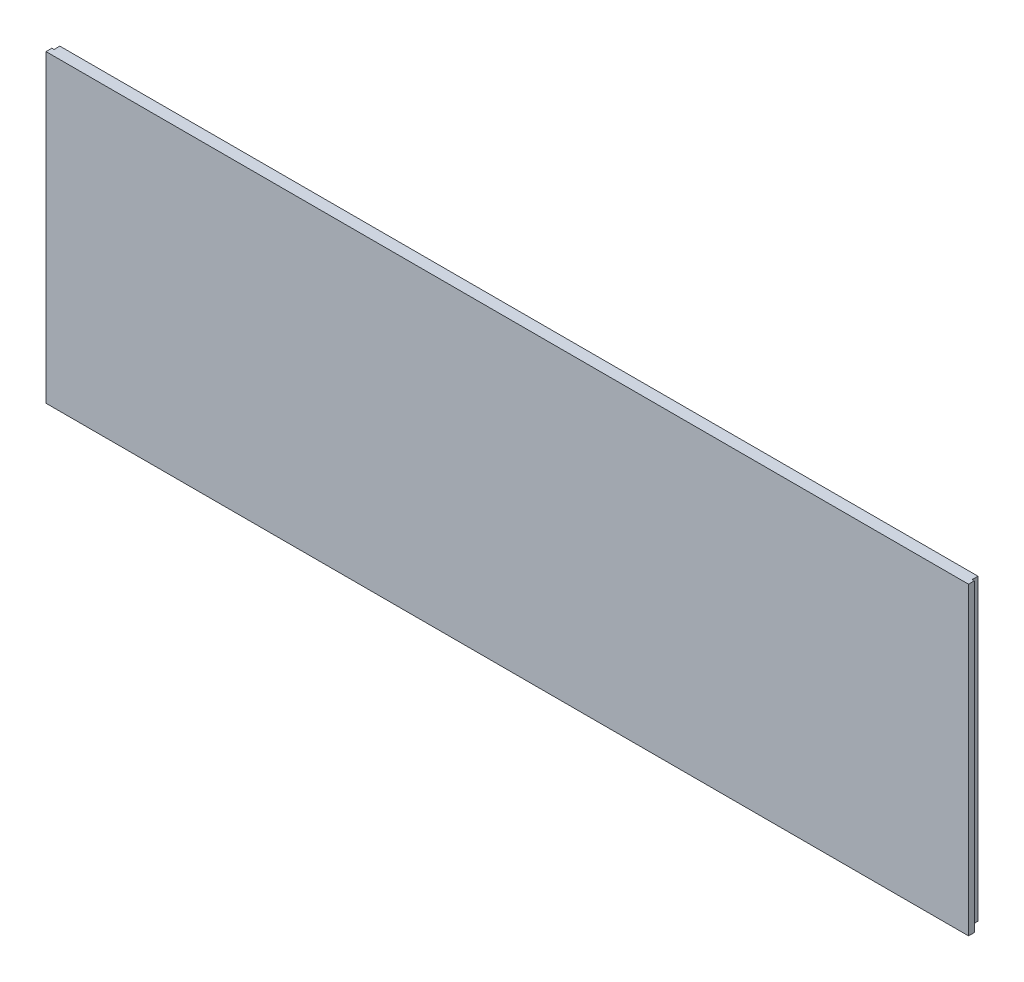
SolidWorks part; units mm, degrees
ref_plane "Front Plane" through (0, 0, 0) normal (0, 0, 1) x (1, 0, 0)
ref_plane "Top Plane" through (0, 0, 0) normal (0, 1, 0) x (1, 0, 0)
ref_plane "Right Plane" through (0, 0, 0) normal (1, 0, 0) x (0, 0, -1)
sketch "Sketch1" plane through (0, 0, 0) normal (0, 0, 1) x (1, 0, 0)
  line L5 (-158.25, 52.25) -> (158.25, 52.25)
  line L6 (-158.25, 52.25) -> (-158.25, -52.25)
  line L7 (-158.25, -52.25) -> (158.25, -52.25)
  line L8 (158.25, 52.25) -> (158.25, -52.25)
  line L9 (-158.25, 52.25) -> (158.25, -52.25) construction
  line L10 (-158.25, -52.25) -> (158.25, 52.25) construction
  point P0 (0, 0)
  dimension "D1" = 104.5
  dimension "D2" = 316.5
extrude "DIGITIZER" add sketch "Sketch1" along normal blind 2
sketch "Sketch2" plane through (0, 0, 0) normal (0, 0, -1) x (-1, 0, 0)
  line L0 (158.25, -52.25) -> (-158.25, -52.25) construction
  line L5 (-157.5, 52.25) -> (157.5, 52.25)
  line L6 (-157.5, 52.25) -> (-157.5, -50.25)
  line L7 (-157.5, -50.25) -> (157.5, -50.25)
  line L8 (157.5, 52.25) -> (157.5, -50.25)
  point P4 (0, 52.25)
  dimension "D1" = 315
  dimension "D2" = 102.5
  dimension "D3" = 2
extrude "DISPLAY WITHOUT MARGIN SINCE USING .2MM ADHESIVE NOW" add sketch "Sketch2" along normal blind 2
sketch "Sketch3" plane through (0, 0, 0) normal (0, 0, -1) x (-1, 0, 0)
  line L0 (-157.5, -50.25) -> (157.5, -50.25) construction
  line L1 (-35, -50.25) -> (35, -50.25)
  line L2 (-35, -50.25) -> (-35, -54.25)
  line L3 (-35, -54.25) -> (35, -54.25)
  line L4 (35, -50.25) -> (35, -54.25)
  line L6 (158.25, -52.25) -> (-158.25, -52.25) construction
  point P8 (0, -50.25)
  dimension "D1" = 70
  dimension "D2" = 2
extrude "DIGITIZER CABLE" add sketch "Sketch3" along normal up to surface (2 mm away) up to face at (0, 1, -2)
